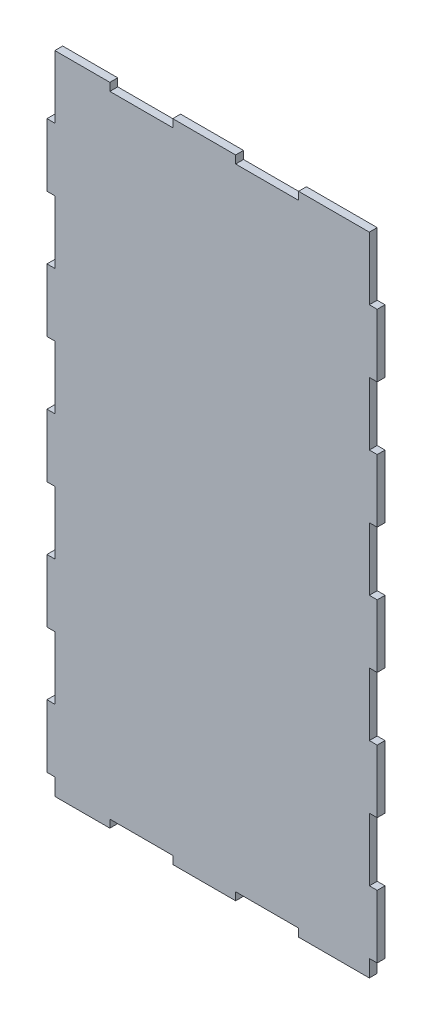
SolidWorks part; units mm, degrees
ref_plane "Front Plane" through (0, 0, 0) normal (0, 0, 1) x (1, 0, 0)
ref_plane "Top Plane" through (0, 0, 0) normal (0, 1, 0) x (1, 0, 0)
ref_plane "Right Plane" through (0, 0, 0) normal (1, 0, 0) x (0, 0, -1)
sketch "Sketch1" plane through (0, 0, 0) normal (0, 0, 1) x (1, 0, 0)
  line L0 (6.35, 521.67) -> (6.35, 470.87)
  line L1 (6.35, 0) -> (260.35, 0) construction
  line L2 (0, 0) -> (0, 521.67) construction
  line L5 (6.35, 13.67) -> (6.35, 0)
  line L7 (6.35, 470.87) -> (0, 470.87)
  line L8 (0, 470.87) -> (0, 420.07)
  line L9 (0, 420.07) -> (6.35, 420.07)
  line L10 (6.35, 420.07) -> (6.35, 369.27)
  line L11 (6.35, 369.27) -> (0, 369.27)
  line L12 (0, 369.27) -> (0, 318.47)
  line L13 (0, 318.47) -> (6.35, 318.47)
  line L14 (6.35, 318.47) -> (6.35, 267.67)
  line L15 (6.35, 267.67) -> (0, 267.67)
  line L16 (0, 267.67) -> (0, 216.87)
  line L17 (0, 216.87) -> (6.35, 216.87)
  line L18 (6.35, 216.87) -> (6.35, 166.07)
  line L19 (6.35, 166.07) -> (0, 166.07)
  line L20 (0, 166.07) -> (0, 115.27)
  line L21 (0, 115.27) -> (6.35, 115.27)
  line L22 (6.35, 115.27) -> (6.35, 64.47)
  line L23 (6.35, 64.47) -> (0, 64.47)
  line L24 (0, 64.47) -> (0, 13.67)
  line L25 (0, 13.67) -> (6.35, 13.67)
  line L26 (6.35, 521.67) -> (0, 521.67) construction
  line L27 (6.35, 0) -> (0, 0) construction
  line L28 (260.35, 521.67) -> (260.35, 470.87)
  line L29 (260.35, 470.87) -> (266.7, 470.87)
  line L30 (266.7, 470.87) -> (266.7, 420.07)
  line L31 (266.7, 420.07) -> (260.35, 420.07)
  line L32 (260.35, 420.07) -> (260.35, 369.27)
  line L33 (260.35, 369.27) -> (266.7, 369.27)
  line L34 (266.7, 369.27) -> (266.7, 318.47)
  line L35 (266.7, 318.47) -> (260.35, 318.47)
  line L36 (260.35, 318.47) -> (260.35, 267.67)
  line L37 (260.35, 267.67) -> (266.7, 267.67)
  line L38 (266.7, 267.67) -> (266.7, 216.87)
  line L39 (266.7, 216.87) -> (260.35, 216.87)
  line L40 (260.35, 216.87) -> (260.35, 166.07)
  line L41 (260.35, 166.07) -> (266.7, 166.07)
  line L42 (266.7, 166.07) -> (266.7, 115.27)
  line L43 (266.7, 115.27) -> (260.35, 115.27)
  line L44 (260.35, 115.27) -> (260.35, 64.47)
  line L45 (260.35, 64.47) -> (266.7, 64.47)
  line L46 (266.7, 64.47) -> (266.7, 13.67)
  line L47 (266.7, 13.67) -> (260.35, 13.67)
  line L48 (260.35, 13.67) -> (260.35, 6.35)
  line L49 (260.35, 521.67) -> (266.7, 521.67) construction
  line L50 (6.35, 0) -> (50.8, 0)
  line L51 (50.8, 0) -> (50.8, 6.35)
  line L52 (50.8, 6.35) -> (101.6, 6.35)
  line L53 (101.6, 6.35) -> (101.6, 0)
  line L54 (101.6, 0) -> (152.4, 0)
  line L55 (152.4, 0) -> (152.4, 6.35)
  line L56 (152.4, 6.35) -> (203.2, 6.35)
  line L57 (203.2, 6.35) -> (203.2, 0)
  line L58 (203.2, 0) -> (254, 0)
  line L59 (254, 0) -> (260.35, 0)
  line L60 (260.35, 0) -> (260.35, 6.35)
  line L61 (6.35, 521.67) -> (50.8, 521.67)
  line L62 (50.8, 521.67) -> (50.8, 515.32)
  line L63 (50.8, 515.32) -> (101.6, 515.32)
  line L64 (101.6, 515.32) -> (101.6, 521.67)
  line L65 (101.6, 521.67) -> (152.4, 521.67)
  line L66 (152.4, 521.67) -> (152.4, 515.32)
  line L67 (152.4, 515.32) -> (203.2, 515.32)
  line L68 (203.2, 515.32) -> (203.2, 521.67)
  line L69 (203.2, 521.67) -> (254, 521.67)
  line L70 (254, 521.67) -> (260.35, 521.67)
  point P3 (0, 0)
  point P4 (133.35, 260.835)
  point P73 (6.35, 521.67)
  dimension "D1" = 266.7
  dimension "D2" = 521.67
  dimension "D3" = 50.8
  dimension "D4" = 6.35
  dimension "D5" = 5
  dimension "D6" = 50.8
  dimension "D7" = 6.35
  dimension "D8" = 6.35
  dimension "D10" = 44.45
  dimension "D11" = 6.35
  dimension "D12" = 50.8
  dimension "D13" = 6.35
  dimension "D14" = 521.67
  dimension "D9" = 5
extrude "Boss-Extrude1" add sketch "Sketch1" along normal blind 6.35
